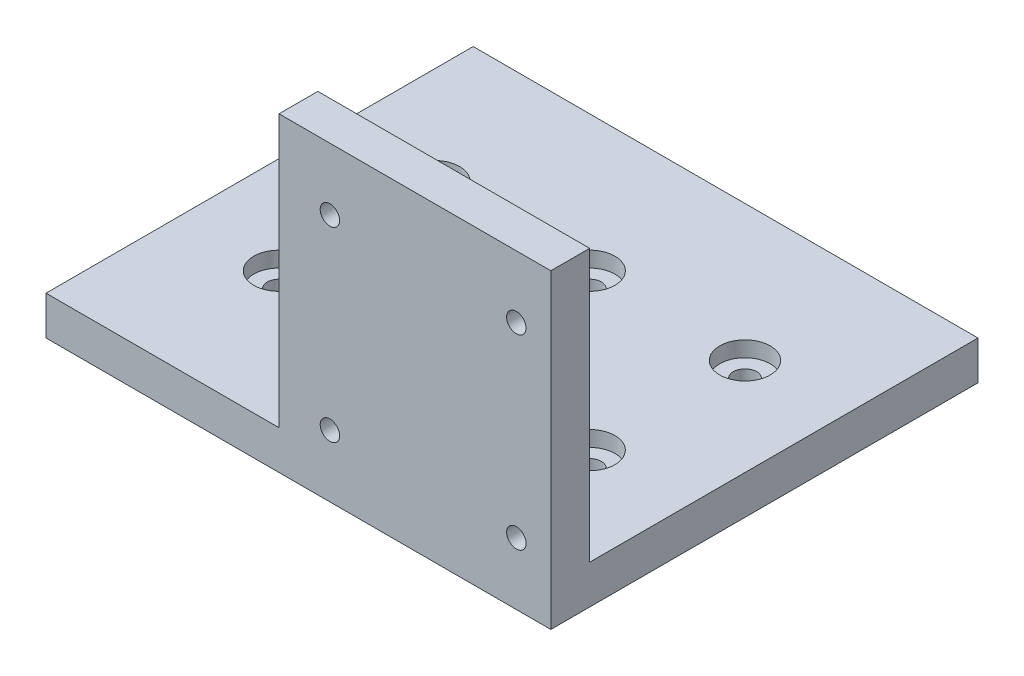
SolidWorks part; units mm, degrees
ref_plane "Front Plane" through (0, 0, 0) normal (0, 0, 1) x (1, 0, 0)
ref_plane "Top Plane" through (0, 0, 0) normal (0, 1, 0) x (1, 0, 0)
ref_plane "Right Plane" through (0, 0, 0) normal (1, 0, 0) x (0, 0, -1)
sketch "Sketch1" plane through (0, 0, 0) normal (0, 1, 0) x (1, 0, 0)
  line L1 (-32.5, -27.5) -> (32.5, -27.5)
  line L2 (-32.5, -27.5) -> (-32.5, 27.5)
  line L3 (-32.5, 27.5) -> (32.5, 27.5)
  line L4 (32.5, -27.5) -> (32.5, 27.5)
  line L5 (-32.5, -27.5) -> (32.5, 27.5) construction
  line L6 (-32.5, 27.5) -> (32.5, -27.5) construction
  point P0 (0, 0)
  dimension "D1" = 55
  dimension "D2" = 65
extrude "Boss-Extrude1" add sketch "Sketch1" along normal blind 5
sketch "Sketch2" plane through (0, 5, 0) normal (0, 1, 0) x (1, 0, 0)
  line L0 (-20, 10) -> (-32.5, 10) construction
  line L1 (-32.5, 27.5) -> (-32.5, -27.5) construction
  line L2 (20, 10) -> (32.5, 10) construction
  line L3 (32.5, -27.5) -> (32.5, 27.5) construction
  line L4 (0, -2.75) -> (0, 2.75) construction
  line L5 (-20, 10) -> (-20, 27.5) construction
  line L6 (32.5, 27.5) -> (-32.5, 27.5) construction
  line L7 (-20, -10) -> (-20, -27.5) construction
  line L8 (-32.5, -27.5) -> (32.5, -27.5) construction
  circle A0 centre (-20, 10) radius 1.5
  circle A1 centre (0, 10) radius 1.5
  circle A2 centre (20, 10) radius 1.5
  circle A3 centre (-20, -10) radius 1.5
  circle A4 centre (0, -10) radius 1.5
  circle A5 centre (20, -10) radius 1.5
  dimension "D1" = 3
  dimension "D2" = 3
  dimension "D4" = 3
  dimension "D6" = 3
  dimension "D8" = 3
  dimension "D9" = 3
  dimension "D3" = 20
  dimension "D5" = 20
  dimension "D7" = 20
extrude "Cut-Extrude1" cut sketch "Sketch2" against normal blind 5
sketch "Sketch3" plane through (0, 5, 0) normal (0, 1, 0) x (1, 0, 0)
  circle A0 centre (-20, 10) radius 3.25
  dimension "D1" = 6.5
extrude "Cut-Extrude2" cut sketch "Sketch3" against normal blind 2
pattern_linear "LPattern1" count 2 spacing 20 along (0, 0, 1) count 3 spacing 20 along (1, 0, 0) of "Cut-Extrude2"
sketch "Sketch5" plane through (0, 5, 0) normal (0, 1, 0) x (1, 0, 0)
  line L0 (32.5, -27.5) -> (32.5, 27.5) construction
  line L1 (-32.5, -27.5) -> (32.5, -27.5)
  line L2 (-32.5, -27.5) -> (-32.5, -22.5)
  line L3 (-32.5, -22.5) -> (32.5, -22.5)
  line L4 (32.5, -27.5) -> (32.5, -22.5)
  line L6 (-18.7014, -27.5) -> (-2.5, -27.5)
  line L7 (-2.5, -27.5) -> (-2.5, -22.5)
  line L8 (-2.5, -22.5) -> (-18.7014, -22.5)
  line M15 (32.5, -27.5) -> (32.5, 27.5)
  line M18 (-32.5, -27.5) -> (32.5, -27.5)
  dimension "D1" = 5
  dimension "D2" = 35
extrude "Boss-Extrude2" add sketch "Sketch5" along normal blind 35 contours L7 L3 M18 M15
sketch "Sketch6" plane through (0, 0, 27.5) normal (0, 0, 1) x (1, 0, 0)
  line L1 (-32.5, 5) -> (-2.5, 5) construction
  circle A0 centre (4.0553, 32) radius 1.25
  circle A1 centre (4.0553, 8) radius 1.25
  circle A2 centre (28.0553, 32) radius 1.25
  circle A3 centre (28.0553, 8) radius 1.25
  dimension "D1" = 2.5
  dimension "D2" = 2.5
  dimension "D4" = 2.5
  dimension "D5" = 2.5
  dimension "D3" = 24
  dimension "D6" = 24
  dimension "D7" = 24
  dimension "D8" = 24
  dimension "D9" = 3
extrude "Cut-Extrude3" cut sketch "Sketch6" against normal blind 35
